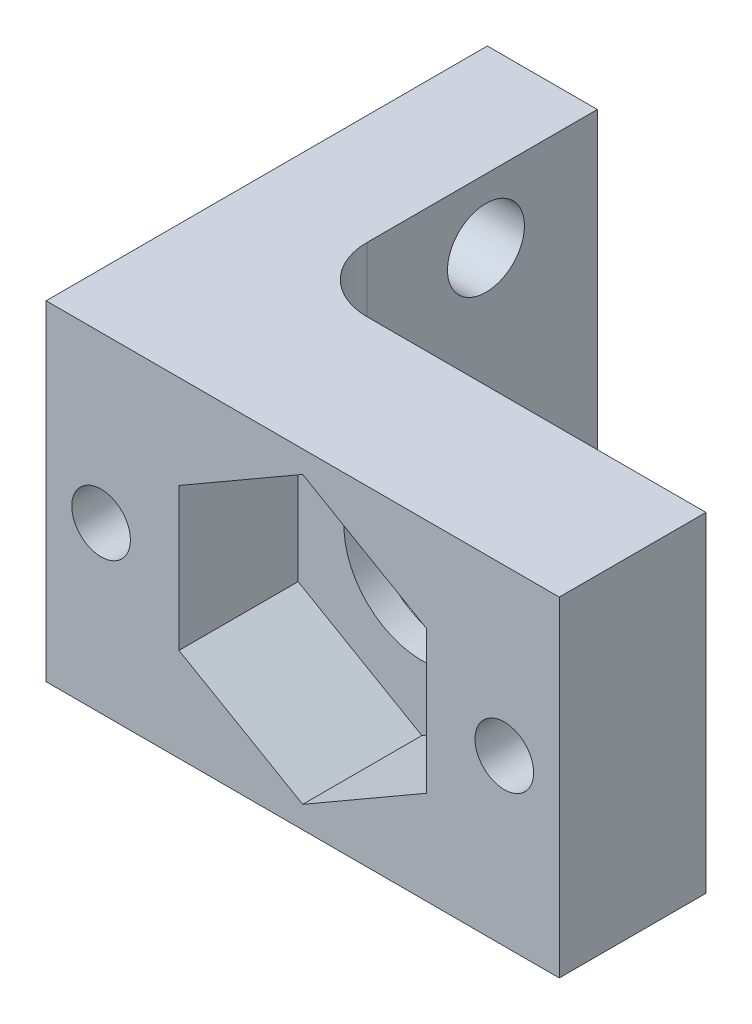
SolidWorks part; units mm, degrees
ref_plane "Front" through (0, 0, 0) normal (0, 0, 1) x (1, 0, 0)
ref_plane "Top" through (0, 0, 0) normal (0, 1, 0) x (1, 0, 0)
ref_plane "Right" through (0, 0, 0) normal (1, 0, 0) x (0, 0, -1)
sketch "Sketch1" plane through (0, 0, 0) normal (0, 1, 0) x (1, 0, 0)
  line L0 (0, 24.0762) -> (0, 0)
  line L1 (0, 0) -> (28, 0)
  line L2 (28, 0) -> (28, 8)
  line L3 (28, 8) -> (6, 8)
  line L4 (6, 8) -> (6, 24.0762)
  line L5 (6, 24.0762) -> (0, 24.0762)
  dimension "D1" = 8
  dimension "D2" = 22
  dimension "D3" = 6
extrude "Boss-Extrude1" add sketch "Sketch1" along normal blind 18
sketch "Sketch3" plane through (0, 0, 0) normal (0, 0, 1) x (1, 0, 0)
  line L0 (0, 18) -> (28, 18) construction
  line L1 (0, 18) -> (0, 0) construction
  line L2 (28, 18) -> (28, 0) construction
  line L3 (20.75, 5.1029) -> (20.75, 12.8971)
  line L4 (20.75, 12.8971) -> (14, 16.7942)
  line L5 (14, 16.7942) -> (7.25, 12.8971)
  line L6 (7.25, 12.8971) -> (7.25, 5.1029)
  line L7 (7.25, 5.1029) -> (14, 1.2058)
  line L8 (14, 1.2058) -> (20.75, 5.1029)
  circle A0 centre (14, 9) radius 6.75 construction
  dimension "D1" = 13.5
  dimension "D2" = 9
  dimension "D3" = 14
extrude "Cut-Extrude1" cut sketch "Sketch3" against normal blind 6.5
sketch "Sketch4" plane through (0, 0, 0) normal (0, 0, 1) x (1, 0, 0)
  line L0 (0, 18) -> (28, 18) construction
  line L1 (28, 18) -> (28, 0) construction
  line L2 (0, 18) -> (0, 0) construction
  circle A0 centre (25, 9) radius 1.6
  circle A1 centre (3, 9) radius 1.6
  dimension "D1" = 9
  dimension "D2" = 3.2
  dimension "D3" = 3
  dimension "D4" = 3
extrude "Cut-Extrude2" cut sketch "Sketch4" against normal blind 17
sketch "Sketch5" plane through (0, 0, 0) normal (-1, 0, 0) x (0, 0, 1)
  line L0 (-24.0762, 18) -> (0, 18) construction
  line L1 (-14, 12) -> (-12, 12)
  line L2 (-14, 12) -> (-14, 6)
  line L3 (-14, 6) -> (-12, 6)
  line L4 (-12, 12) -> (-12, 6)
  line L5 (0, 18) -> (0, 0) construction
  dimension "D1" = 6
  dimension "D2" = 2
  dimension "D3" = 6
  dimension "D4" = 12
extrude "Cut-Extrude3" cut sketch "Sketch5" against normal blind 6
sketch "Sketch6" plane through (0, 0, -6.5) normal (0, 0, 1) x (1, 0, 0)
  line L0 (20.75, 5.1029) -> (20.75, 12.8971) construction
  line L3 (7.25, 5.1029) -> (14, 1.2058) construction
  line L4 (14, 16.7942) -> (7.25, 12.8971) construction
  circle A0 centre (14, 9) radius 6.75 construction
  circle A1 centre (14, 9) radius 4.25
  dimension "D1" = 8.5
extrude "Cut-Extrude4" cut sketch "Sketch6" against normal blind 6
fillet "Fillet1" radius 3.5 1 edges at (6, 9, -8)
sketch "Sketch7" plane through (6, 0, 0) normal (1, 0, 0) x (0, 0, -1)
  line L0 (11.5, 18) -> (24.0762, 18) construction
  line L2 (0, 18) -> (0, 0) construction
  line L3 (26.7565, 9) -> (14.71, 9) construction
  circle A0 centre (18, 14.5) radius 2.1
  circle A1 centre (18, 3.5) radius 2.1
  dimension "D1" = 4.2
  dimension "D2" = 3.5
  dimension "D3" = 18
  dimension "D4" = 9
extrude "Cut-Extrude5" cut sketch "Sketch7" against normal blind 6
